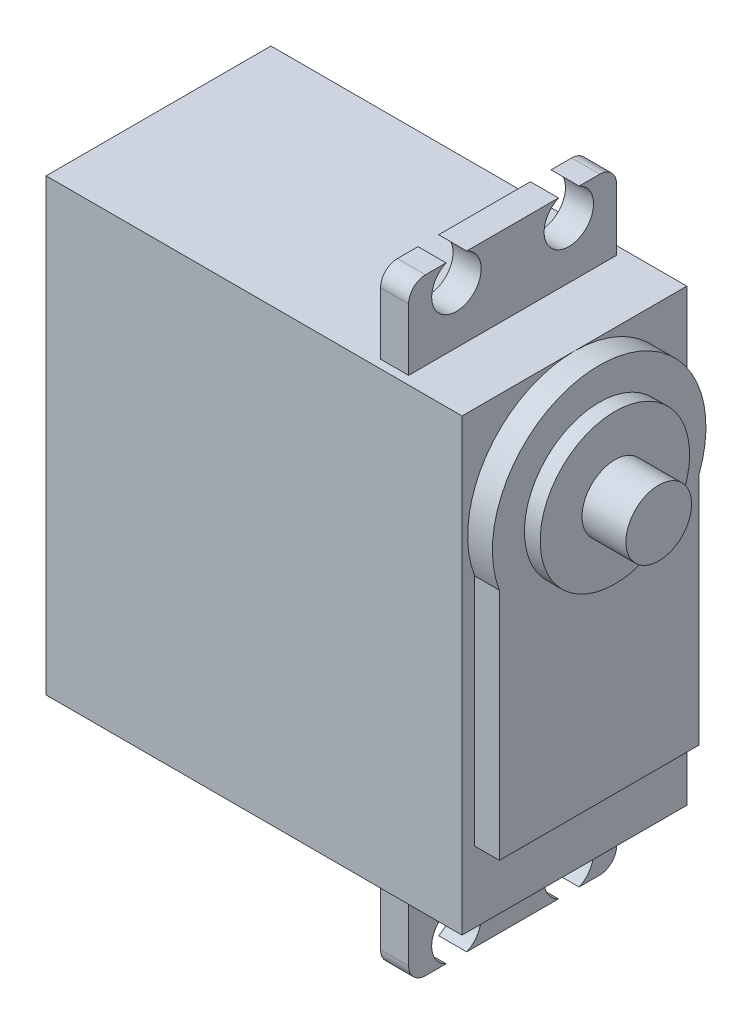
SolidWorks part; units mm, degrees
ref_plane "Front Plane" through (0, 0, 0) normal (0, 0, 1) x (1, 0, 0)
ref_plane "Top Plane" through (0, 0, 0) normal (0, 1, 0) x (1, 0, 0)
ref_plane "Right Plane" through (0, 0, 0) normal (1, 0, 0) x (0, 0, -1)
sketch "Sketch1" plane through (0, 0, 0) normal (0, 0, 1) x (1, 0, 0)
  line L1 (-18.5, 20) -> (18.5, 20)
  line L2 (-18.5, 20) -> (-18.5, -20)
  line L3 (-18.5, -20) -> (18.5, -20)
  line L4 (18.5, 20) -> (18.5, -20)
  line L5 (-18.5, 20) -> (18.5, -20) construction
  line L6 (-18.5, -20) -> (18.5, 20) construction
  point P0 (0, 0)
  dimension "D1" = 40
  dimension "36.7" = 37
extrude "Boss-Extrude1" add sketch "Sketch1" against normal blind 20
ref_plane "Plane1" through (10.5, 0, 0) normal (-1, 0, 0) x (0, 0, 1)
sketch "Sketch2" plane through (10.5, 0, 0) normal (-1, 0, 0) x (0, 0, 1)
  line L0 (-10, 20) -> (-10, -20) construction
  line L1 (-20, 20) -> (0, 20) construction
  line L2 (-20, 0) -> (4.0027, 0) construction
  line L3 (-20, 20) -> (-20, -20) construction
  line L5 (-19.25, -27) -> (-0.75, -27)
  line L6 (-19.25, -27) -> (-19.25, 27)
  line L7 (-19.25, 27) -> (-0.75, 27)
  line L8 (-0.75, -27) -> (-0.75, 27)
  line L9 (-19.25, -27) -> (-0.75, 27) construction
  line L10 (-19.25, 27) -> (-0.75, -27) construction
  point P9 (-10, 0)
  dimension "D1" = 18.5
  dimension "D2" = 27
  dimension "D3" = 27
extrude "Boss-Extrude2" add sketch "Sketch2" against normal blind 2.5
fillet "Fillet1" radius 1.5 4 edges at (11.75, -27, -0.75) (11.75, -27, -19.25) (11.75, 27, -19.25) (11.75, 27, -0.75)
sketch "Sketch3" plane through (13, 0, 0) normal (1, 0, 0) x (0, 0, -1)
  line L0 (0.75, 20) -> (19.25, 20) construction
  line L3 (10, 27) -> (10, 20.6993) construction
  line L4 (2.25, 27) -> (17.75, 27) construction
  line L5 (19.25, -20) -> (0.75, -20) construction
  line L6 (0, 0) -> (17.0489, 0) construction
  circle A0 centre (5, 25) radius 2.2
  circle A1 centre (15, 25) radius 2.2
  circle A2 centre (5, -25) radius 2.2
  circle A3 centre (15, -25) radius 2.2
  point P14 (0, 0)
  dimension "D1" = 4.4
  dimension "D2" = 5
  dimension "D3" = 10
  dimension "D4" = 5
  dimension "D5" = 5
extrude "Cut-Extrude1" cut sketch "Sketch3" against normal up to next
sketch "Sketch4" plane through (18.5, 0, 0) normal (1, 0, 0) x (0, 0, -1)
  line L0 (10, 20) -> (10, -4.3844) construction
  line L1 (0.75, 20) -> (19.25, 20) construction
  line L2 (20, 20) -> (0, 20) construction
  circle A0 centre (10, 10.5) radius 9.5
  dimension "D1" = 19
  dimension "D2" = 9.5
extrude "Boss-Extrude3" add sketch "Sketch4" along normal blind 2.2
sketch "Sketch5" plane through (18.5, 0, 0) normal (1, 0, 0) x (0, 0, -1)
  line L0 (10, -20) -> (10, 2.4788) construction
  line L1 (19.25, -20) -> (0.75, -20) construction
  line L3 (1.125, -13.7) -> (18.875, -13.7)
  line L4 (1.125, -13.7) -> (1.125, 10.1042)
  line L5 (1.125, 10.1042) -> (18.875, 10.1042)
  line L6 (18.875, -13.7) -> (18.875, 10.1042)
  line L7 (1.125, -13.7) -> (18.875, 10.1042) construction
  line L8 (1.125, 10.1042) -> (18.875, -13.7) construction
  point P4 (10, -1.7979)
  dimension "D1" = 6.3
  dimension "D2" = 17.75
extrude "Boss-Extrude4" add sketch "Sketch5" along normal blind 2.2
sketch "Sketch6" plane through (20.7, 0, 0) normal (1, 0, 0) x (0, 0, -1)
  line L0 (10, 20) -> (10, -2.2125) construction
  line L1 (0.75, 20) -> (19.25, 20) construction
  arc A0 (18.875, 7.1111) -> (1.125, 7.1111) centre (10, 10.5) ccw construction
  circle A1 centre (10, 10.5) radius 6.65
  dimension "D2" = 13.3
  dimension "D1" = 9.5
extrude "Boss-Extrude5" add sketch "Sketch6" along normal blind 1.4
sketch "Sketch7" plane through (22.1, 0, 0) normal (1, 0, 0) x (0, 0, -1)
  circle A0 centre (10, 10.5) radius 2.925
  dimension "D1" = 5.85
extrude "Boss-Extrude6" add sketch "Sketch7" along normal blind 3.9
